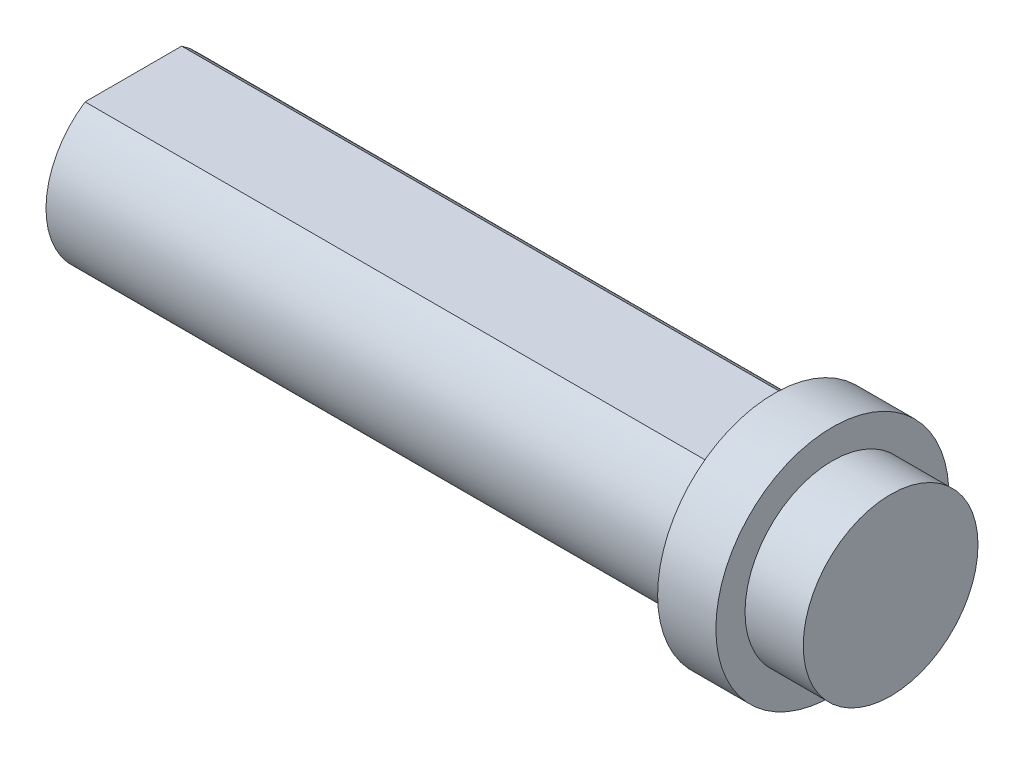
SolidWorks part; units mm, degrees
ref_plane "前视基准面" through (0, 0, 0) normal (0, 0, 1) x (1, 0, 0)
ref_plane "上视基准面" through (0, 0, 0) normal (0, 1, 0) x (1, 0, 0)
ref_plane "右视基准面" through (0, 0, 0) normal (1, 0, 0) x (0, 0, -1)
sketch "Sketch1" plane through (0, 0, 0) normal (1, 0, 0) x (0, 0, -1)
  circle A0 centre (0, 0) radius 3
extrude "Boss-Extrude1" add sketch "Sketch1" along normal blind 26
sketch "Sketch2" plane through (0, 0, 0) normal (-1, 0, 0) x (0, 0, 1)
  line L0 (-0.8359, 2.5) -> (1.1857, 2.5) construction
  line L1 (-1.6583, 2.5) -> (1.6583, 2.5)
  arc A0 (1.6583, 2.5) -> (-1.6583, 2.5) centre (0, 0) ccw
  dimension "D1" = 2.5
extrude "Cut-Extrude1" cut sketch "Sketch2" against normal blind 22
ref_plane "Plane1" through (22, 0, 0) normal (-1, 0, 0) x (0, 0, 1)
sketch "Sketch3" plane through (22, 0, 0) normal (-1, 0, 0) x (0, 0, 1)
  circle A0 centre (0, 0) radius 3
  circle A1 centre (0, 0) radius 4
  dimension "D1" = 8
extrude "Boss-Extrude2" add sketch "Sketch3" against normal blind 2
sketch "Sketch4" plane through (0, 0, 0) normal (0, 0, 1) x (1, 0, 0)
  line L0 (21.5, 2.5) -> (22, 2.75)
  line L1 (22, 2.5) -> (0, 2.5) construction
  line L2 (22, 4) -> (22, -4) construction
  line L3 (22, 2.75) -> (22, 2.5)
  line L4 (22, 2.5) -> (21.5, 2.5)
  dimension "D1" = 0.5
  dimension "D2" = 0.25
extrude "Boss-Extrude3" add sketch "Sketch4" along normal mid plane 3.32
